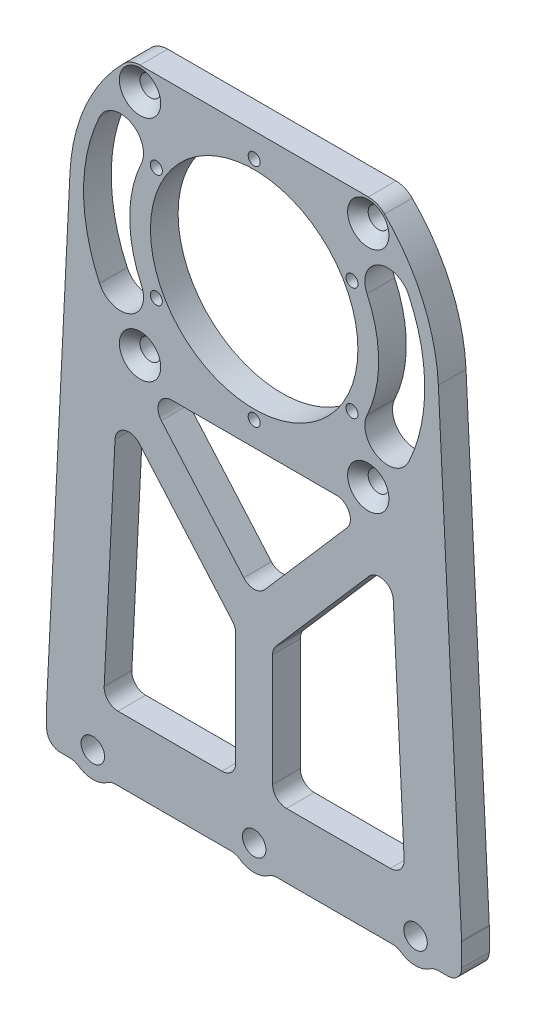
SolidWorks part; units mm, degrees
material "Thornel Mat VMA"
ref_plane "前视基准面" through (0, 0, 0) normal (0, 0, 1) x (1, 0, 0)
ref_plane "上视基准面" through (0, 0, 0) normal (0, 1, 0) x (1, 0, 0)
ref_plane "右视基准面" through (0, 0, 0) normal (1, 0, 0) x (0, 0, -1)
sketch "草图1" plane through (0, 0, 0) normal (0, 0, 1) x (1, 0, 0)
  line L0 (-45, 0) -> (-39.9511, 101.978)
  line L1 (-45, 0) -> (45, 0)
  line L2 (-45, 0) -> (-45, -8)
  line L3 (-45, -8) -> (45, -8)
  line L4 (45, 0) -> (45, -8)
  line L5 (-45, 0) -> (45, -8) construction
  line L6 (-45, -8) -> (45, 0) construction
  line L7 (0, 100) -> (0, 0) construction
  line L8 (45, 0) -> (39.9511, 101.978)
  line L9 (0, 100) -> (0, 135) construction
  line L10 (0, 100) -> (-35, 100) construction
  line L11 (0, 100) -> (-13.435, 113.435) construction
  circle A0 centre (0, 100) radius 40
  circle A1 centre (0, 100) radius 22.5
  circle A2 centre (0, 100) radius 35 construction
  circle A8 centre (0, 100) radius 24.5 construction
  circle A9 centre (0, 124.5) radius 1.3
  circle A10 centre (21.2176, 112.25) radius 1.3
  circle A11 centre (21.2176, 87.75) radius 1.3
  circle A12 centre (0, 75.5) radius 1.3
  circle A13 centre (-21.2176, 87.75) radius 1.3
  circle A14 centre (-21.2176, 112.25) radius 1.3
  circle A15 centre (0, 100) radius 19 construction
  circle A16 centre (-13.435, 113.435) radius 1.3 construction
  circle A17 centre (13.435, 113.435) radius 1.3 construction
  circle A18 centre (13.435, 86.565) radius 1.3 construction
  circle A19 centre (-13.435, 86.565) radius 1.3 construction
  circle A20 centre (-24.7487, 124.7487) radius 2.1
  circle A21 centre (24.7487, 124.7487) radius 2.1
  circle A22 centre (24.7487, 75.2513) radius 2.1
  circle A23 centre (-24.7487, 75.2513) radius 2.1
  point P2 (0, -4)
  point P8 (0, 0)
  point P26 (0, 100)
  point P41 (0, 100)
  point P51 (0, 100)
  point P52 (0, 100)
  point P60 (0, 100)
  dimension "D4" = 45
  dimension "D5" = 80
  dimension "D6" = 70
  dimension "D8" = 4.2
  dimension "D11" = 49
  dimension "D12" = 2.6
  dimension "D14" = 38
  dimension "D16" = 2.6
  dimension "D1" = 100
  dimension "D2" = 8
  dimension "D3" = 90
  dimension "D7" = 90
  dimension "D15" = 45
  dimension "D13" = 6
  dimension "D17" = 4
  dimension "D9" = 4
extrude "凸台-拉伸1" add sketch "草图1" along normal blind 6
hole_wizard "M4 六角凹锥坑螺钉的锥形沉头孔1" positions "草图2" profile "草图3" countersink size "M4" standard "ISO"
sketch "草图2" plane through (0, 0, 6) normal (0, 0, 1) x (1, 0, 0)
  point P0 (-24.7487, 124.7487)
  point P3 (24.7487, 124.7487)
  point P6 (24.7487, 75.2513)
  point P9 (-24.7487, 75.2513)
sketch "草图3" plane through (-24.7487, 124.7487, 6) normal (1, 0, 0) x (0, -1, 0)
  line L0 (0, 0) -> (0, 12.7519)
  line L1 (0, 12.7519) -> (2.25, 11.4)
  line L2 (2.25, 11.4) -> (2.25, 2.23)
  line L3 (2.25, 2.23) -> (4.48, 0)
  line L5 (4.48, 0) -> (0, 0)
  line L6 (-2.25, 2.23) -> (-4.48, 0) construction
  line L10 (0, 12.7519) -> (-2.25, 11.4) construction
  line L11 (0, -6.35) -> (0, 107.95) construction
  dimension "孔直径" = 4.5
  dimension "孔深度" = 11.4
  dimension "近端锥形沉头孔直径" = 8.96
  dimension "近端锥形沉头孔角度" = 90
  dimension "导头角度" = 118
sketch "草图4" plane through (0, 0, 6) normal (0, 0, 1) x (1, 0, 0)
  line L0 (-35, -4) -> (35, -4) construction
  line L1 (-45, -8) -> (45, -8) construction
  line L2 (0, 0) -> (0, -4) construction
  circle A0 centre (-35, -4) radius 2.55
  circle A1 centre (0, -4) radius 2.55
  circle A2 centre (35, -4) radius 2.55
  dimension "D3" = 5.1
  dimension "D1" = 4
  dimension "D2" = 70
extrude "切除-拉伸1" cut sketch "草图4" against normal through all
sketch "草图5" plane through (0, 0, 6) normal (0, 0, 1) x (1, 0, 0)
  line L0 (45, -8) -> (-45, -8)
  circle A0 centre (35, -4) radius 2.55 construction
  circle A1 centre (0, -4) radius 2.55 construction
  circle A2 centre (-35, -4) radius 2.55 construction
  circle A3 centre (35, -4) radius 2.55
  circle A4 centre (0, -4) radius 2.55
  circle A5 centre (-35, -4) radius 2.55
  circle A6 centre (35, -4) radius 5.55
  circle A7 centre (0, -4) radius 5.55
  circle A8 centre (-35, -4) radius 5.55
  dimension "D1" = 3
extrude "凸台-拉伸2" add sketch "草图5" against normal up to surface (6 mm away) contours L0 A8 | L0 A7 | L0 A6 up to face at (-32.45, -4, 0)
sketch "草图6" plane through (0, 0, 6) normal (0, 0, 1) x (1, 0, 0)
  line L0 (-29.7487, 129.7487) -> (-29.7487, 70.2513)
  line L1 (-24.7487, 124.7487) -> (24.7487, 124.7487) construction
  line L2 (-24.7487, 124.7487) -> (-24.7487, 75.2513) construction
  line L3 (-24.7487, 75.2513) -> (24.7487, 75.2513) construction
  line L4 (24.7487, 124.7487) -> (24.7487, 75.2513) construction
  line L5 (-24.7487, 124.7487) -> (24.7487, 75.2513) construction
  line L6 (-24.7487, 75.2513) -> (24.7487, 124.7487) construction
  line L7 (-29.7487, 70.2513) -> (29.7487, 70.2513)
  line L8 (29.7487, 129.7487) -> (29.7487, 70.2513)
  line L9 (-29.7487, 129.7487) -> (29.7487, 129.7487)
  line L10 (-27.9657, 101.3846) -> (-32.6882, 6)
  line L11 (32.6882, 6) -> (27.9657, 101.3846)
  line L12 (80.1665, 6) -> (44.7029, 6)
  line L13 (-27.9657, 101.3846) -> (-33.0147, -0.5934) construction
  line L14 (32.6882, 6) -> (-32.6882, 6)
  line L15 (33.0147, -0.5934) -> (27.9657, 101.3846) construction
  line L16 (-29.7487, 70.2513) -> (0, 36)
  line L17 (0, 36) -> (0, 6)
  line L19 (45, 0) -> (39.9511, 101.978)
  line L22 (-39.9511, 101.978) -> (-45, 0)
  line L24 (-45, 0) -> (-45, -8)
  line L34 (-45, -8) -> (-38.8474, -8)
  line L35 (-31.1526, -8) -> (-3.8474, -8)
  line L36 (3.8474, -8) -> (31.1526, -8)
  line L37 (38.8474, -8) -> (45, -8)
  line L38 (45, -8) -> (45, 0)
  line L39 (45, 0) -> (39.9511, 101.978)
  line L40 (-39.9511, 101.978) -> (-45, 0)
  line L41 (-45, 0) -> (-45, -8)
  line L42 (-45, -8) -> (-38.8474, -8)
  line L43 (-31.1526, -8) -> (-3.8474, -8)
  line L44 (3.8474, -8) -> (31.1526, -8)
  line L45 (38.8474, -8) -> (45, -8)
  line L46 (45, -8) -> (45, 0)
  line L47 (29.7487, 70.2513) -> (0, 36)
  line L48 (-26.7288, 72.8742) -> (3.0199, 38.623)
  line L49 (32.7687, 67.6283) -> (3.0199, 33.377)
  line L50 (4, 36) -> (4, 6)
  line L51 (-32.7687, 67.6283) -> (-3.0199, 33.377)
  line L52 (26.7288, 72.8742) -> (-3.0199, 38.623)
  line L53 (-4, 36) -> (-4, 6)
  arc A12 (39.9511, 101.978) -> (-39.9511, 101.978) centre (0, 100) ccw
  arc A13 (-38.8474, -8) -> (-31.1526, -8) centre (-35, -4) ccw
  arc A14 (-3.8474, -8) -> (3.8474, -8) centre (0, -4) ccw
  arc A15 (31.1526, -8) -> (38.8474, -8) centre (35, -4) ccw
  arc A16 (39.9511, 101.978) -> (-39.9511, 101.978) centre (0, 100) ccw
  arc A17 (-38.8474, -8) -> (-31.1526, -8) centre (-35, -4) ccw
  arc A18 (-3.8474, -8) -> (3.8474, -8) centre (0, -4) ccw
  arc A19 (31.1526, -8) -> (38.8474, -8) centre (35, -4) ccw
  point P0 (0, 100)
  arc M35 (39.9511, 101.978) -> (-39.9511, 101.978) centre (0, 100) ccw
  dimension "D3" = 12
  dimension "D4" = 14
  dimension "D7" = 30
  dimension "D1" = 5
  dimension "D2" = 0
  dimension "D5" = 4
  dimension "D6" = 4
extrude "切除-拉伸3" cut sketch "草图6" against normal through all contours L9 M35 | L49 L50 L14 L11 | L53 L51 L10 L14 | L52 L7 L48
fillet "圆角1" radius 5 2 edges at (26.7397, 129.7487, 3) (-26.7397, 129.7487, 3)
fillet "圆角2" radius 3 11 edges at (0, 42.1, 3) (-24.4506, 70.2513, 3) (32.6882, 6, 3) (4, 6, 3) (4, 34.5054, 3) (29.8059, 64.2171, 3) (-4, 6, 3) (-32.6882, 6, 3) (-29.8059, 64.2171, 3) (-4, 34.5054, 3) (24.4506, 70.2513, 3)
fillet "圆角4" radius 3 10 edges at (45, 0, 3) (38.8474, -8, 3) (31.1526, -8, 3) (3.8474, -8, 3) (-3.8474, -8, 3) (-31.1526, -8, 3) (-38.8474, -8, 3) (-45, -8, 3) (-45, 0, 3) (45, -8, 3)
sketch "草图7" plane through (0, 0, 6) normal (0, 0, 1) x (1, 0, 0)
  line L0 (0, 100) -> (32, 100) construction
  line L1 (29.0018, 113.5238) -> (0, 100) construction
  line L2 (0, 100) -> (29.0018, 86.4762) construction
  line L3 (0, 100) -> (0, 68) construction
  circle A0 centre (0, 100) radius 32 construction
  arc A1 (29.0018, 113.5238) -> (29.0018, 86.4762) centre (0, 100) cw construction
  arc A2 (33.5334, 84.3631) -> (33.5334, 115.6369) centre (0, 100) ccw
  arc A3 (24.4703, 88.5893) -> (24.4703, 111.4107) centre (0, 100) ccw
  arc A4 (24.4703, 88.5893) -> (33.5334, 84.3631) centre (29.0018, 86.4762) ccw
  arc A5 (33.5334, 115.6369) -> (24.4703, 111.4107) centre (29.0018, 113.5238) ccw
  arc A6 (-29.0018, 113.5238) -> (-29.0018, 86.4762) centre (0, 100) ccw construction
  arc A7 (-33.5334, 84.3631) -> (-33.5334, 115.6369) centre (0, 100) cw
  arc A8 (-24.4703, 88.5893) -> (-24.4703, 111.4107) centre (0, 100) cw
  arc A9 (-24.4703, 88.5893) -> (-33.5334, 84.3631) centre (-29.0018, 86.4762) cw
  arc A10 (-33.5334, 115.6369) -> (-24.4703, 111.4107) centre (-29.0018, 113.5238) cw
  point P5 (32, 100)
  point P17 (-32, 100)
  dimension "D1" = 64
  dimension "D3" = 5
  dimension "D2" = 50
extrude "切除-拉伸4" cut sketch "草图7" against normal through all
